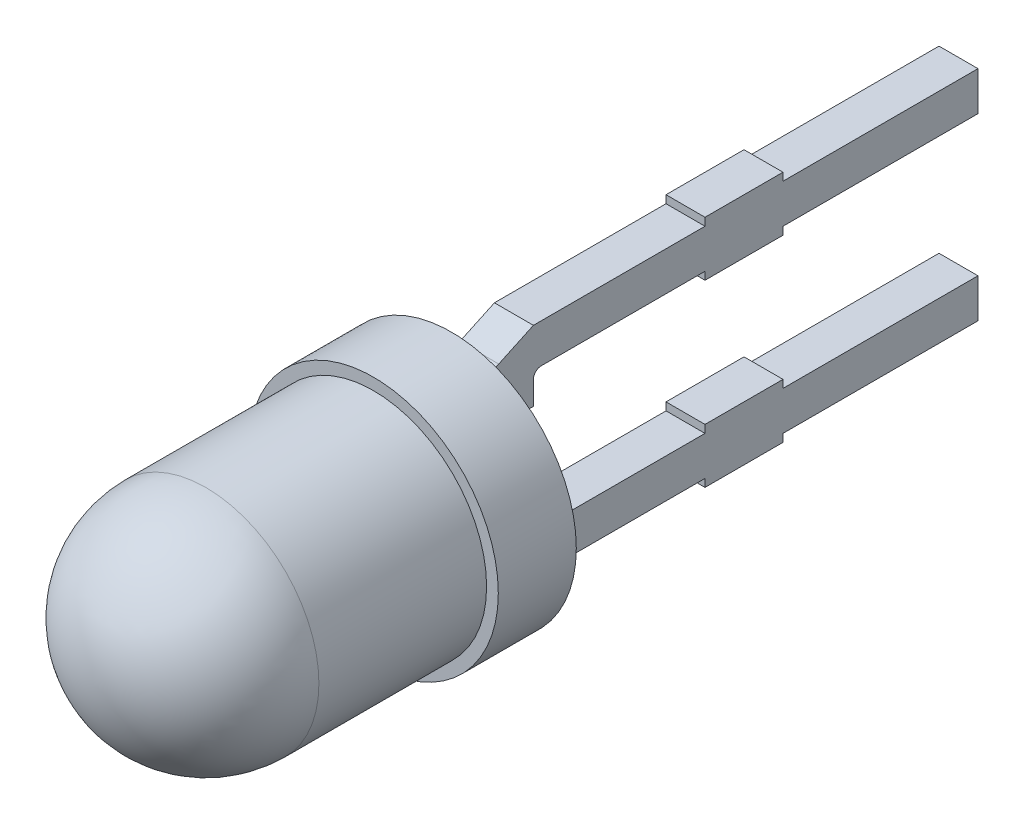
SolidWorks part; units mm, degrees
ref_plane "Front" through (0, 0, 0) normal (0, 0, 1) x (1, 0, 0)
ref_plane "Top" through (0, 0, 0) normal (0, 1, 0) x (1, 0, 0)
ref_plane "Right" through (0, 0, 0) normal (1, 0, 0) x (0, 0, -1)
sketch "Sketch1" plane through (0, 0, 0) normal (1, 0, 0) x (0, 0, -1)
  line L0 (0, 0) -> (76.2974, 0) construction
  line L1 (0, 1.45) -> (2.15, 1.45)
  line L2 (2.15, 1.45) -> (2.15, 1.6)
  line L3 (2.15, 1.6) -> (3.15, 1.6)
  line L4 (3.15, 1.6) -> (3.15, 0)
  line L5 (3.15, 0) -> (-1.45, 0)
  arc A0 (0, 1.45) -> (-1.45, 0) centre (0, 0) ccw
  dimension "D1" = 1.45
  dimension "D2" = 4.6
  dimension "D3" = 1
  dimension "D4" = 1.6
revolve "Revolve1" add sketch "Sketch1" angle 360 about L0
sketch "Sketch2" plane through (0, 0, 0) normal (1, 0, 0) x (0, 0, -1)
  line L0 (3.15, -1.6) -> (3.15, 1.6) construction
  line L1 (3.15, -1.6) -> (3.15, 1.6) construction
  line L2 (3.15, 1.027) -> (3.95, 1.4)
  line L3 (3.95, 1.4) -> (6.15, 1.4)
  line L4 (6.15, 1.4) -> (6.15, 1.5)
  line L5 (6.15, 1.5) -> (7.15, 1.5)
  line L6 (7.15, 1.5) -> (7.15, 1.4)
  line L7 (7.15, 1.4) -> (30.15, 1.4)
  line L8 (30.15, 1.4) -> (30.15, 0.9)
  line L9 (30.15, 0.9) -> (7.15, 0.9)
  line L10 (7.15, 0.9) -> (7.15, 0.8)
  line L11 (7.15, 0.8) -> (6.15, 0.8)
  line L12 (6.15, 0.8) -> (6.15, 0.9)
  line L13 (6.15, 0.9) -> (4.05, 0.9)
  line L14 (3.95, 0.8) -> (3.95, 0.5)
  line L15 (3.95, 0.5) -> (3.15, 0.5)
  line L16 (3.15, 0) -> (7.9733, 0) construction
  line L17 (3.15, 1.027) -> (3.15, 0.5)
  line L18 (3.95, -0.8) -> (3.95, -0.5)
  line L19 (6.15, -0.9) -> (4.05, -0.9)
  line L20 (6.15, -0.8) -> (6.15, -0.9)
  line L21 (7.15, -0.8) -> (6.15, -0.8)
  line L22 (7.15, -0.9) -> (7.15, -0.8)
  line L23 (30.15, -0.9) -> (7.15, -0.9)
  line L24 (30.15, -1.4) -> (30.15, -0.9)
  line L25 (7.15, -1.4) -> (30.15, -1.4)
  line L26 (7.15, -1.5) -> (7.15, -1.4)
  line L27 (6.15, -1.5) -> (7.15, -1.5)
  line L28 (6.15, -1.4) -> (6.15, -1.5)
  line L29 (3.95, -1.4) -> (6.15, -1.4)
  line L30 (3.15, -1.027) -> (3.95, -1.4)
  line L31 (3.15, -1.027) -> (3.15, -0.5)
  line L32 (3.95, -0.5) -> (3.15, -0.5)
  arc A0 (4.05, 0.9) -> (3.95, 0.8) centre (4.05, 0.8) ccw
  arc A1 (4.05, -0.9) -> (3.95, -0.8) centre (4.05, -0.8) cw
  point P19 (3.15, 0)
  dimension "D1" = 0.5
  dimension "D2" = 0.7
  dimension "D3" = 1.4
  dimension "D4" = 0.8
  dimension "D5" = 27
  dimension "D6" = 115
  dimension "D7" = 4
  dimension "D8" = 1
  dimension "D9" = 0.5
  dimension "D10" = 0.1
extrude "Extrude1" add sketch "Sketch2" along normal mid plane 0.5
fillet "Fillet1" radius 0.25 8 edges at (0, -0.5, -3.15) (0, -1.027, -3.15) (-0.25, -0.7635, -3.15) (0, 0.5, -3.15) (-0.25, 0.7635, -3.15) (0, 1.027, -3.15) (0.25, 0.7635, -3.15) (0.25, -0.7635, -3.15)
sketch "Sketch3" plane through (0, 0, 0) normal (1, 0, 0) x (0, 0, -1)
  line L0 (7.15, -1.4) -> (30.15, -1.4) construction
  line L1 (30.15, 1.4) -> (18.15, 1.4)
  line L2 (30.15, 1.4) -> (30.15, -1.4)
  line L3 (30.15, -1.4) -> (18.15, -1.4)
  line L4 (18.15, 1.4) -> (18.15, -1.4)
  line L5 (3.15, -1.6) -> (3.15, 1.6) construction
  dimension "D1" = 15
extrude "Cut-Extrude1" cut sketch "Sketch3" against normal through all both and the other way through all
sketch "Sketch4" plane through (0, 0, 0) normal (1, 0, 0) x (0, 0, -1)
  line L0 (3.15, -1.6) -> (3.15, 1.6) construction
  line L1 (9.65, 2.534) -> (19.0404, 2.534)
  line L2 (9.65, 2.534) -> (9.65, -2.5001)
  line L3 (9.65, -2.5001) -> (19.0404, -2.5001)
  line L4 (19.0404, 2.534) -> (19.0404, -2.5001)
  dimension "D1" = 6.5
extrude "Cut-Extrude2" cut sketch "Sketch4" against normal through all both and the other way through all
